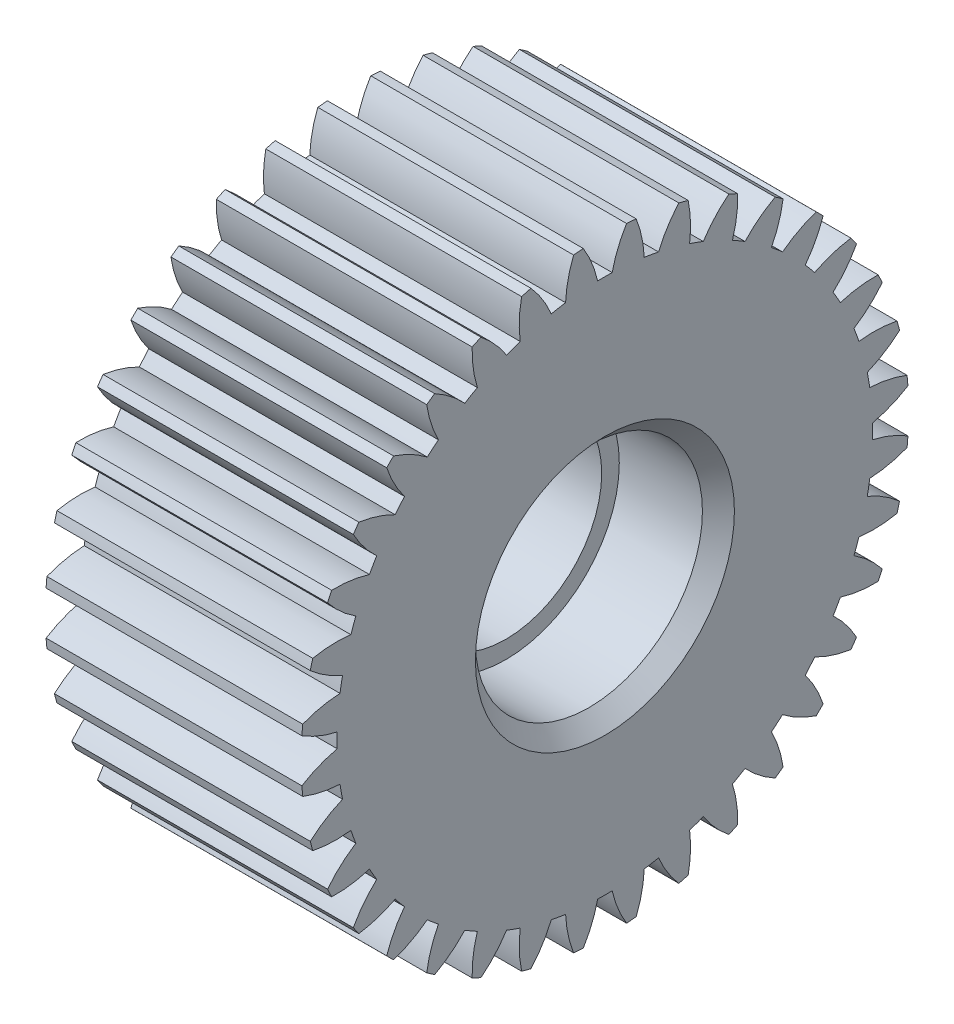
SolidWorks part; units mm, degrees
ref_plane "Plane1" through (0, 0, 0) normal (0, 0, 1) x (1, 0, 0)
ref_plane "Plane2" through (0, 0, 0) normal (0, 1, 0) x (1, 0, 0)
ref_plane "Plane3" through (0, 0, 0) normal (1, 0, 0) x (0, 0, -1)
sketch "HoldingSke" plane through (0, 0, 0) normal (0, 1, 0) x (1, 0, 0)
  line L0 (0, 0) -> (1.618, -1.1756)
  line L1 (-15, 0) -> (100, 0) construction
  line L2 (0, 0) -> (-2.1039, 2.3779)
  line L3 (0, 0) -> (-11.863, 4.5341)
  line L4 (0, 0) -> (6.9867, 5.0761)
  line L5 (0, 0) -> (-46.8476, -17.4728)
  line L6 (0, 0) -> (-6.6317, -4.4744)
  line L7 (-2.1039, 2.3779) -> (8.6586, 51.2059)
  line L8 (-76.2, 54.61) -> (-75.9, 54.61)
  line L9 (-71.009, 38.7566) -> (-53.1078, 45.2721)
  line L10 (-76.2, 71.12) -> (104.1128, 71.12)
  line L11 (0, 0) -> (-8, 0)
  line L12 (-76.2, 101.6) -> (-76.181, 101.6)
  line L13 (24.9733, 27.94) -> (52.9518, 28.4284)
  line L14 (24.9733, 27.94) -> (24.9743, 27.94)
  line L15 (24.9733, 27.94) -> (100.4006, 29.5858)
  line L16 (-63.627, -0.5) -> (-12.827, -0.5)
  circle A0 centre (0, 0) radius 1
  circle A1 centre (0, 0) radius 8.374
  circle A2 centre (0, 0) radius 37.5
  circle A3 centre (0, 0) radius 1
  dimension "MHD" = 16.748
  dimension "Hub_dia" = 75
  dimension "Bore" = 2
  dimension "MBD" = 2
  dimension "Num_teeth" = 36
  dimension "Pitch" = 2
  dimension "Overall_len" = 50
  dimension "Show_teeth" = 36
  dimension "Thickness" = 8
  dimension "OAL" = 50.0001
  dimension "T_dim" = 0.3
  dimension "Ap" = 20
  dimension "H" = 19.05
  dimension "Pitch_radius" = 180.3128
  dimension "Width" = 8
  dimension "Backlash" = 0.019
  dimension "Addendum_fac" = 1
  dimension "Dedendum_fac" = 1.25
  dimension "Clearance_fac" = 0.25
  dimension "Dedendum_add" = 0.001
  dimension "Module" = 0.5
sketch "BasProSke" plane through (0, 0, 0) normal (0, 1, 0) x (1, 0, 0)
  line L0 (-10, 0) -> (60, 0) construction
  line L1 (0, 0) -> (0, 9.5)
  line L2 (0, 0) -> (8, 0)
  line L3 (8, 0) -> (8, 9.5)
  line L4 (8, 9.5) -> (0, 9.5)
  dimension "Thickness" = 8
  dimension "Diameter" = 19
revolve "Base-Revolve" add sketch "BasProSke" angle 360 about L0
sketch "TooCutSke" plane through (0, 0, 0) normal (1, 0, 0) x (0, 0, -1)
  line L1 (0, 0) -> (0, 107) construction
  line L2 (0, 0) -> (-0.4258, 8.9899) construction
  line L3 (0, 0) -> (-1.5676, 17.9172) construction
  line L4 (-0.4258, 8.9899) -> (-0.7838, 8.9586) construction
  arc A0 (0.2272, 8.3709) -> (-0.2272, 8.3709) centre (0, 0) ccw
  arc A1 (0.6921, 9.5002) -> (-0.6921, 9.5002) centre (0, 0) ccw
  circle A2 centre (0, 0) radius 9 construction
  circle A3 centre (0, 0) radius 8.4572 construction
  arc A4 (-0.2272, 8.3709) -> (-0.6921, 9.5002) centre (-3.7404, 7.5851) ccw
  arc A5 (0.6921, 9.5002) -> (0.2272, 8.3709) centre (3.7404, 7.5851) ccw
  dimension "Root_dia" = 16.748
  dimension "Overcut_dia" = 19.0508
  dimension "Pitch_dia" = 18
  dimension "Base_dia" = 16.9145
  dimension "Flank_rad" = 3.6
  dimension "Half_ang" = 5
  dimension "Half_CT" = 0.3593
extrude "ToothCut" cut sketch "TooCutSke" along normal through all
fillet "Breaks" [suppressed] radius 0.01
fillet "RootFillets" [suppressed] radius 0.126
pattern_circular "TeethCuts" count 36 every 10 about axis through (-10, 0, 0) along (1, 0, 0) of "ToothCut", "RootFillets", "Breaks"
sketch "HubNeaOneSke" plane through (0, 0, 0) normal (-1, 0, 0) x (0, 0, 1)
  circle A0 centre (0, 0) radius 8.374
  dimension "Diameter" = 16.748
extrude "HubNearOne" [suppressed] add sketch "HubNeaOneSke" along normal blind 42.0001
sketch "HubNeaBotSke" plane through (0, 0, 0) normal (-1, 0, 0) x (0, 0, 1)
  circle A0 centre (0, 0) radius 8.374
  dimension "Diameter" = 16.748
extrude "HubNearBoth" [suppressed] add sketch "HubNeaBotSke" along normal blind 21
ref_plane "FarPln" through (8, 0, 0) normal (1, 0, 0) x (0, 0, -1)
sketch "HubFarSke" plane through (8, 0, 0) normal (1, 0, 0) x (0, 0, -1)
  circle A0 centre (0, 0) radius 8.374
  dimension "Diameter" = 16.748
extrude "HubFar" [suppressed] add sketch "HubFarSke" along normal blind 21
sketch "BorSke" plane through (0, 0, 0) normal (1, 0, 0) x (0, 0, -1)
  circle A0 centre (0, 0) radius 1
  dimension "Diameter" = 2
extrude "Bore" cut sketch "BorSke" along normal mid plane 100.0001
sketch "KeySke" plane through (0, 0, 0) normal (1, 0, 0) x (0, 0, -1)
  line L0 (-0.4, 0) -> (-0.4, 1.3)
  line L1 (-0.4, 1.3) -> (0.4, 1.3)
  line L2 (0.4, 1.3) -> (0.4, 0)
  line L3 (0, 0) -> (0, 34) construction
  line L4 (-0.4, 0) -> (0.4, 0)
  dimension "Offset" = 1.3
extrude "Keyway" [suppressed] cut sketch "KeySke" along normal mid plane 100.0001
pattern_circular "Keyway2" [suppressed] count 2 every 90 about axis through (-10, 0, 0) along (1, 0, 0)
sketch "Sketch1" plane through (0, 0, 0) normal (0, 1, 0) x (1, 0, 0)
  line L0 (0, 3) -> (4.9, 3)
  line L1 (4.9, 3) -> (4.9, 3.55)
  line L2 (4.9, 3.55) -> (8, 3.55)
  line L3 (8, 3.55) -> (8, 0)
  line L4 (8, 0) -> (0, 0)
  line L5 (0, 0) -> (0, 3)
  line L6 (-4.6723, 0) -> (-11.6778, 0) construction
  line L7 (8, -0.2272) -> (8, 0.2272) construction
  point P2 (10.0171, 2.6421)
  point P8 (0, 0)
  dimension "D1" = 3.1
  dimension "D2" = 7.1
  dimension "D3" = 6
revolve "Cut-Revolve1" cut sketch "Sketch1" angle 360 about L6
chamfer "Chamfer1" distance 0.5 angle 45 1 edges at (8, 0, -3.55)
equation "' \"Module@HoldingSke\" = 6.35"
equation "' \"Num_teeth@HoldingSke\" = 12"
equation "' \"Ap@HoldingSke\" =  20"
equation "' \"Ap@HoldingSke\" = 20"
equation "' \"Width@HoldingSke\" = 0.5 * 25.4"
equation "' \"Hub_dia@HoldingSke\"= 1 * 25.4"
equation "' \"Hub_dia@HoldingSke\" = 1 * 25.4"
equation "' \"Overall_len@HoldingSke\" = 1.0 * 25.4"
equation "' \"Bore@HoldingSke\" = 0.75 * 25.4"
equation "' \"T_dim@HoldingSke\" = 0.1 * 25.4"
equation "' \"Width@KeySke\" = 0.25 * 25.4"
equation "' \"Show_teeth@HoldingSke\" = 13"
equation "' \"Backlash@HoldingSke\" = 0.009 * 25.4"
equation "' \"Addendum_fac@HoldingSke\" = 1.0"
equation "' \"Dedendum_fac@HoldingSke\" = 1.25"
equation "' \"Dedendum_add@HoldingSke\" = 0.00005 * 25.4"
equation "' \"Clearance_fac@HoldingSke\" = 0.25"
equation "\"Pitch@HoldingSke\" = 1 / \"Module@HoldingSke\""
equation "\"Overcut_dia@TooCutSke\" = (\"Num_teeth@HoldingSke\" + 2 * \"Addendum_fac@HoldingSke\") / \"Pitch@HoldingSke\" + 0.002 * 25.4"
equation "\"Pitch_dia@TooCutSke\" = \"Num_teeth@HoldingSke\" / \"Pitch@HoldingSke\""
equation "\"Base_dia@TooCutSke\" = \"Num_teeth@HoldingSke\" / \"Pitch@HoldingSke\" * cos((\"Ap@HoldingSke\"  * 3.14159265 / 180))"
equation "\"Root_dia@TooCutSke\" = (\"Num_teeth@HoldingSke\" + 2) / \"Pitch@HoldingSke\" - 2 * (\"Addendum_fac@HoldingSke\" + \"Dedendum_fac@HoldingSke\") / \"Pitch@HoldingSke\" - \"Dedendum_add@HoldingSke\" * 2"
equation "\"Half_ang@TooCutSke\" = 180 / \"Num_teeth@HoldingSke\""
equation "\"Half_CT@TooCutSke\" = \"Num_teeth@HoldingSke\" / \"Pitch@HoldingSke\" * sin((3.14159265 / 2 / \"Num_teeth@HoldingSke\")) / 2 - 7 * \"Backlash@HoldingSke\" / 4"
equation "\"Flank_rad@TooCutSke\" = \"Num_teeth@HoldingSke\" / \"Pitch@HoldingSke\" / 5"
equation "\"Radius@RootFillets\" = \"Clearance_fac@HoldingSke\" / \"Pitch@HoldingSke\" + \"Dedendum_add@HoldingSke\""
equation "\"Break_rad@Breaks\" = 0.02 / \"Pitch@HoldingSke\""
equation "\"Thickness@HoldingSke\" = \"Width@HoldingSke\""
equation "\"OAL@HoldingSke\" = \"Thickness@HoldingSke\""
equation "\"MHD@HoldingSke\" = (\"Num_teeth@HoldingSke\" + 2) / \"Pitch@HoldingSke\" - 2 * (\"Addendum_fac@HoldingSke\" + \"Dedendum_fac@HoldingSke\")  / \"Pitch@HoldingSke\" - \"Dedendum_add@HoldingSke\" * 2"
equation "\"MBD@HoldingSke\" = (\"Num_teeth@HoldingSke\" + 2) / \"Pitch@HoldingSke\" - 2 * (\"Addendum_fac@HoldingSke\" + \"Dedendum_fac@HoldingSke\")  / \"Pitch@HoldingSke\" - \"Dedendum_add@HoldingSke\" * 2 - 0.002 * 25.4"
equation "\"MHD@HoldingSke\" = ((sgn( \"MHD@HoldingSke\" - \"Hub_dia@HoldingSke\" )-1)*( \"MHD@HoldingSke\" - \"Hub_dia@HoldingSke\" ))/-2+ \"Hub_dia@HoldingSke\""
equation "\"MBD@HoldingSke\" = ((sgn( \"MBD@HoldingSke\" - \"Bore@HoldingSke\" )-1)*( \"MBD@HoldingSke\" - \"Bore@HoldingSke\" ))/-2+ \"Bore@HoldingSke\""
equation "\"OAL@HoldingSke\" = ((sgn( \"OAL@HoldingSke\" - \"Overall_len@HoldingSke\" )+1)*( \"OAL@HoldingSke\" - \"Overall_len@HoldingSke\" ))/2 + \"Overall_len@HoldingSke\" + 0.000002 * 25.4"
equation "\"Num_teeth@TeethCuts\" = int( \"Show_teeth@HoldingSke\" ) + 1"
equation "\"Num_teeth@TeethCuts\" = ((sgn( \"Num_teeth@TeethCuts\" - \"Num_teeth@HoldingSke\" )-1)*( \"Num_teeth@TeethCuts\" - \"Num_teeth@HoldingSke\" ))/-2+ \"Num_teeth@HoldingSke\""
equation "\"Num_teeth@TeethCuts\" = ((sgn( \"Num_teeth@TeethCuts\" - 2.0)+1)*( \"Num_teeth@TeethCuts\" - 2.0))/2 +2.0"
equation "\"Angle@TeethCuts\" = 360.0 / \"Num_teeth@HoldingSke\""
equation "\"Diameter@BasProSke\" = (\"Num_teeth@HoldingSke\" + 2 * \"Addendum_fac@HoldingSke\") / \"Pitch@HoldingSke\""
equation "\"Thickness@BasProSke\"  = \"Thickness@HoldingSke\""
equation "' \"Fillet_rad@BasProSke\" =  \"Thickness@HoldingSke\" * 0.05"
equation "' \"Fillet_rad@BasProSke\" = \"Thickness@HoldingSke\" * 0.05"
equation "\"MHD@HoldingSke\" = ((sgn( \"MHD@HoldingSke\" - \"Root_dia@TooCutSke\" )-1)*( \"MHD@HoldingSke\" - \"Root_dia@TooCutSke\" ))/-2+ \"Root_dia@TooCutSke\""
equation "\"Diameter@HubNeaOneSke\" = \"MHD@HoldingSke\""
equation "\"Length@HubNearOne\" = \"OAL@HoldingSke\" - \"Thickness@BasProSke\""
equation "\"Diameter@HubNeaBotSke\" = \"MHD@HoldingSke\""
equation "\"Length@HubNearBoth\" = ( \"OAL@HoldingSke\" - \"Thickness@BasProSke\" ) / 2.0"
equation "\"Thickness@FarPln\" = \"Thickness@BasProSke\""
equation "\"Diameter@HubFarSke\" = \"MHD@HoldingSke\""
equation "\"Length@HubFar\" = ( \"OAL@HoldingSke\" - \"Thickness@BasProSke\" ) / 2.0"
equation "\"Diameter@BorSke\" = \"MBD@HoldingSke\""
equation "\"D1@Bore\" = \"OAL@HoldingSke\" * 2.0"
equation "\"D1@Keyway\" = \"OAL@HoldingSke\" * 2.0"
equation "\"Offset@KeySke\" = \"T_dim@HoldingSke\" + \"MBD@HoldingSke\" / 2.0"
